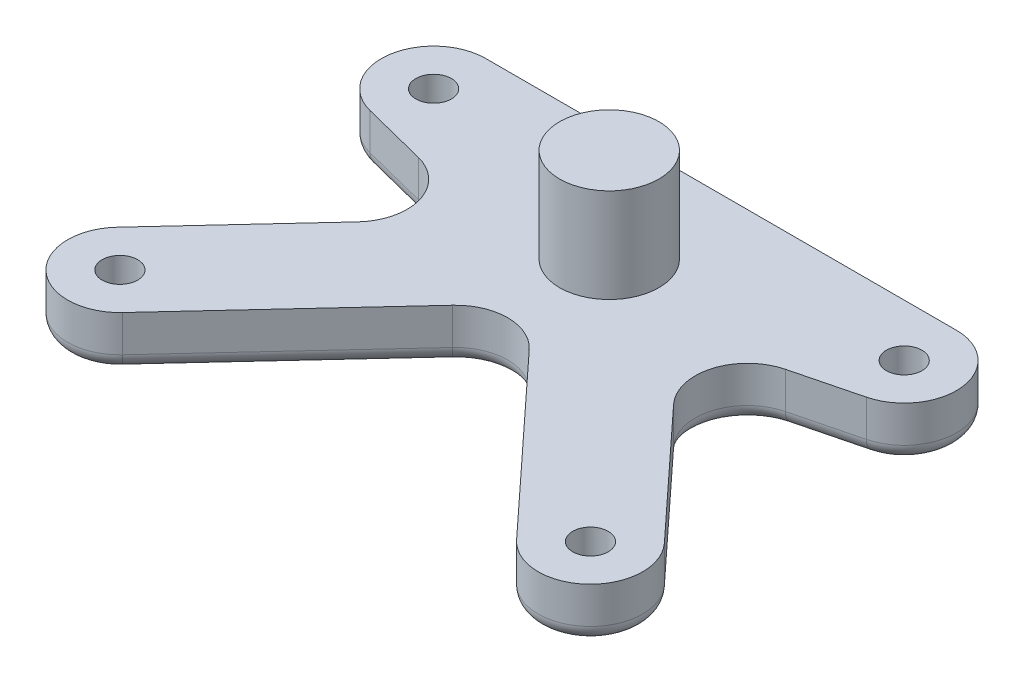
SolidWorks part; units mm, degrees
ref_plane "Front Plane" through (0, 0, 0) normal (0, 0, 1) x (1, 0, 0)
ref_plane "Top Plane" through (0, 0, 0) normal (0, 1, 0) x (1, 0, 0)
ref_plane "Right Plane" through (0, 0, 0) normal (1, 0, 0) x (0, 0, -1)
sketch "Sketch1" plane through (0, 0, 0) normal (0, 1, 0) x (1, 0, 0)
  line L0 (22.5, 15) -> (-22.5, 15) construction
  line L1 (-22.5, 15) -> (-22.5, -15) construction
  line L2 (-22.5, -15) -> (22.5, -15) construction
  line L3 (22.5, -15) -> (22.5, 15) construction
  line L4 (-22.5, -15) -> (0, 9.3) construction
  line L5 (-26.1688, -11.603) -> (-15.1071, 0.3436)
  line L6 (-18.8312, -18.397) -> (-3.6688, -2.0217)
  line L7 (0, 9.3) -> (22.5, -15) construction
  line L10 (22.5, 15) -> (0, 9.3) construction
  line L11 (23.7279, 10.1531) -> (17.5481, 8.5876)
  line L13 (-22.5, 15) -> (0, 9.3) construction
  line L15 (-23.7279, 10.1531) -> (-17.5481, 8.5876)
  line L16 (-22.5, 20) -> (22.5, 20)
  line L17 (15.1071, 0.3436) -> (26.1688, -11.603)
  line L18 (3.6688, -2.0217) -> (18.8312, -18.397)
  circle A0 centre (22.5, 15) radius 1.7
  circle A1 centre (22.5, -15) radius 1.7
  circle A2 centre (-22.5, 15) radius 1.7
  circle A3 centre (-22.5, -15) radius 1.7
  circle A4 centre (0, 9.3) radius 4.75 construction
  arc A5 (-26.1688, -11.603) -> (-18.8312, -18.397) centre (-22.5, -15) ccw
  arc A8 (18.8312, -18.397) -> (26.1688, -11.603) centre (22.5, -15) ccw
  arc A9 (23.7279, 10.1531) -> (22.5, 20) centre (22.5, 15) ccw
  arc A11 (-22.5, 20) -> (-23.7279, 10.1531) centre (-22.5, 15) ccw
  arc A12 (15.1071, 0.3436) -> (17.5481, 8.5876) centre (18.7759, 3.7407) cw
  arc A13 (-15.1071, 0.3436) -> (-17.5481, 8.5876) centre (-18.7759, 3.7407) ccw
  arc A14 (3.6688, -2.0217) -> (-3.6688, -2.0217) centre (0, -5.4187) ccw
  point P7 (-22.5, 0)
  point P9 (-11.25, -2.85)
  point P11 (0, 15)
  point P18 (11.25, -2.85)
  point P24 (11.25, 12.15)
  point P30 (-11.25, 12.15)
  dimension "D1" = 3.4
  dimension "D2" = 3.4
  dimension "D3" = 3.4
  dimension "D4" = 3.4
  dimension "D7" = 9.5
  dimension "D9" = 5
  dimension "D10" = 5
  dimension "D11" = 5
  dimension "D12" = 5
  dimension "D13" = 5
  dimension "D14" = 5
  dimension "D5" = 45
  dimension "D6" = 30
  dimension "D8" = 24.3
  dimension "D15" = 37.5519
  dimension "D16" = 5.5593
  dimension "D17" = 6.1798
  dimension "D18" = 1.5656
  dimension "D19" = 1.5656
  dimension "D20" = 6.1798
  dimension "D21" = 11.9466
  dimension "D22" = 11.9466
  dimension "D23" = 85.595
  dimension "D24" = 15.1624
  dimension "D25" = 16.3754
  dimension "D26" = 15.1624
extrude "Boss-Extrude1" add sketch "Sketch1" along normal blind 5
sketch "Sketch2" plane through (0, 5, 0) normal (0, 1, 0) x (1, 0, 0)
  circle A0 centre (0, 9.3) radius 4.75
  circle A1 centre (-22.5, -15) radius 1.7 construction
  dimension "D1" = 9.5
  dimension "D2" = 24.3
extrude "Boss-Extrude2" add sketch "Sketch2" along normal blind 9
fillet "Fillet1" radius 1.5 14 edges at (27.4616, 0, -15.6187) (20.638, 0, -9.3703) (13.9817, 0, -5.1602) (20.638, 0, 5.6297) (25.897, 0, 18.6688) (11.25, 0, 10.2093) (0, 0, 0.4187) (-11.25, 0, 10.2093) (-25.897, 0, 18.6688) (-20.638, 0, 5.6297) (-13.9817, 0, -5.1602) (-20.638, 0, -9.3703) (-27.4616, 0, -15.6187) (0, 0, -20)
